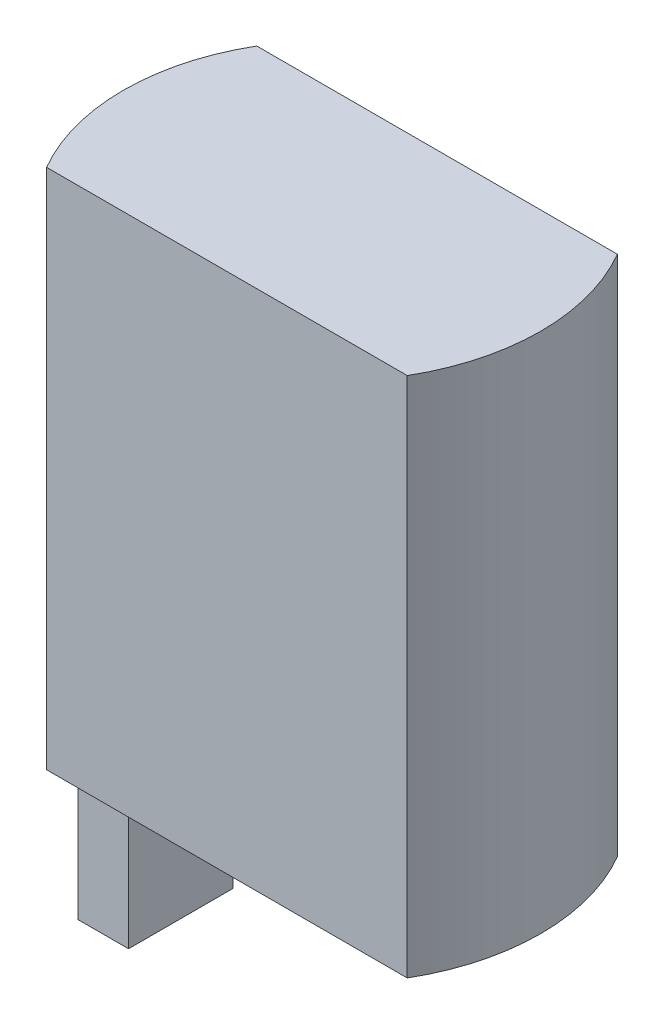
SolidWorks part; units mm, degrees
ref_plane "Front Plane" through (0, 0, 0) normal (0, 0, 1) x (1, 0, 0)
ref_plane "Top Plane" through (0, 0, 0) normal (0, 1, 0) x (1, 0, 0)
ref_plane "Right Plane" through (0, 0, 0) normal (1, 0, 0) x (0, 0, -1)
sketch "Sketch1" plane through (0, 0, 0) normal (0, 1, 0) x (1, 0, 0)
  circle A0 centre (0, 0) radius 10
  dimension "D1" = 20
extrude "Boss-Extrude1" add sketch "Sketch1" along normal blind 25
sketch "Sketch2" plane through (0, 0, 0) normal (0, -1, 0) x (-1, 0, 0)
  line L1 (8.05, 2.5) -> (7.25, 2.5)
  line L2 (8.05, 2.5) -> (8.05, -2.5)
  line L3 (8.05, -2.5) -> (7.25, -2.5)
  line L4 (7.25, 2.5) -> (7.25, -2.5)
  point P4 (7.25, 0)
  dimension "D1" = 5
  dimension "D2" = 0.8
  dimension "D3" = 7.25
extrude "Boss-Extrude2" add sketch "Sketch2" along normal blind 8 separate body
sketch "Sketch3" plane through (-8.05, 0, 0) normal (-1, 0, 0) x (0, 0, 1)
  line L0 (-2.5, -8) -> (-2.5, 0)
  line L1 (-2.5, 0) -> (2.5, 0)
  line L2 (2.5, 0) -> (2.5, -8)
  line L3 (2.5, -8) -> (1.5, -8)
  line L4 (2.5, -8) -> (-2.5, -8) construction
  line L5 (1.5, -8) -> (1.5, -0.75)
  line L6 (1.5, -0.75) -> (-1.5, -0.75)
  line L7 (-1.5, -0.75) -> (-1.5, -8)
  line L8 (-1.5, -8) -> (-2.5, -8)
  dimension "D1" = 1
  dimension "D2" = 1
  dimension "D3" = 0.75
extrude "Boss-Extrude3" add sketch "Sketch3" along normal blind 1.2
sketch "Sketch5" plane through (0, 0, 0) normal (0, -1, 0) x (1, 0, 0)
  line L0 (0, 0) -> (0, 10) construction
  line L1 (0, 10) -> (0, -10) construction
  line L2 (-10, 0) -> (10, 0) construction
  line L3 (-8.64, -5.0349) -> (8.64, -5.0349)
  line L4 (-8.64, 5.0349) -> (8.64, 5.0349)
  arc A0 (-8.64, 5.0349) -> (8.64, 5.0349) centre (0, 0) cw
  circle A1 centre (0, 0) radius 10 construction
  arc A2 (-8.64, -5.0349) -> (8.64, -5.0349) centre (0, 0) ccw
  circle A3 centre (0, 0) radius 10 construction
  dimension "D1" = 8.64
  dimension "D3" = 8.64
extrude "Cut-Extrude1" cut sketch "Sketch5" against normal blind 25 contours L3 A2 | L4 A0
sketch "Sketch6" plane through (-9.25, 0, 0) normal (-1, 0, 0) x (0, 0, 1)
  line L1 (-2.5, -8) -> (2.5, -8)
  line L2 (-2.5, -8) -> (-2.5, 0)
  line L3 (-2.5, 0) -> (2.5, 0)
  line L4 (2.5, -8) -> (2.5, 0)
extrude "Boss-Extrude4" add sketch "Sketch6" along normal blind 0.8
sketch "Sketch7" plane through (0, 0, 0) normal (0, 1, 0) x (1, 0, 0)
  line L0 (-9.6825, 2.5) -> (-10.05, 2.5)
  line L1 (-10.05, 2.5) -> (-10.05, -2.5)
  line L2 (-10.05, -2.5) -> (-9.6825, -2.5)
  arc A0 (-9.6825, 2.5) -> (-9.6825, -2.5) centre (0, 0) ccw
extrude "Cut-Extrude2" cut sketch "Sketch7" against normal up to next
